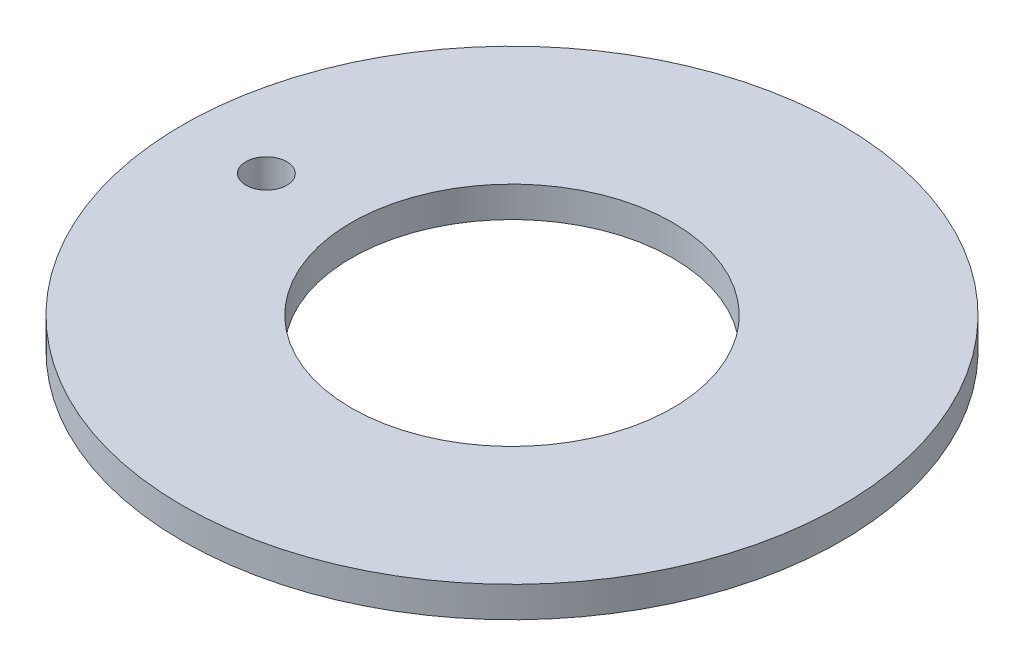
SolidWorks part; units mm, degrees
ref_plane "Front Plane" through (0, 0, 0) normal (0, 0, 1) x (1, 0, 0)
ref_plane "Top Plane" through (0, 0, 0) normal (0, 1, 0) x (1, 0, 0)
ref_plane "Right Plane" through (0, 0, 0) normal (1, 0, 0) x (0, 0, -1)
sketch "Sketch1" plane through (0, 0, 0) normal (0, 1, 0) x (1, 0, 0)
  circle A0 centre (0, 0) radius 15.7
  circle A1 centre (0, 0) radius 32.2
  dimension "D1" = 31.4
  dimension "D2" = 64.4
extrude "Boss-Extrude1" add sketch "Sketch1" along normal blind 3
sketch "Sketch2" plane through (0, 3, 0) normal (0, 1, 0) x (1, 0, 0)
  circle A0 centre (0, 0) radius 24 construction
  circle A3 centre (-24, 0) radius 2
  dimension "D1" = 48
  dimension "D2" = 4
extrude "Cut-Extrude1" cut sketch "Sketch2" against normal through all
